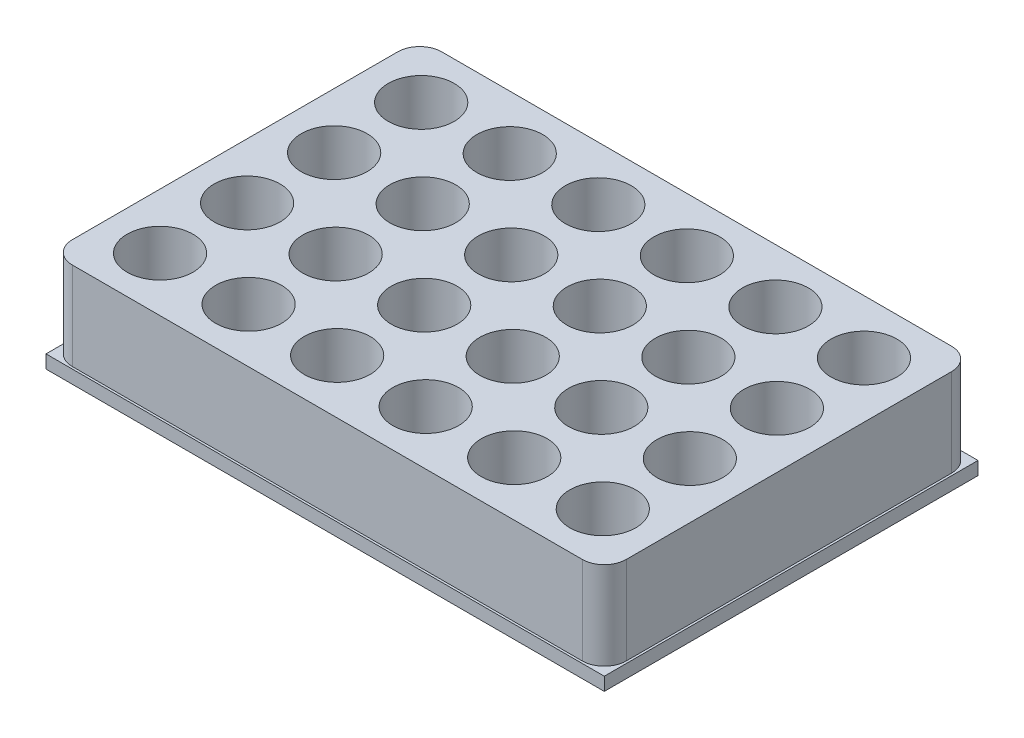
SolidWorks part; units mm, degrees
ref_plane "Front Plane" through (0, 0, 0) normal (0, 0, 1) x (1, 0, 0)
ref_plane "Top Plane" through (0, 0, 0) normal (0, 1, 0) x (1, 0, 0)
ref_plane "Right Plane" through (0, 0, 0) normal (1, 0, 0) x (0, 0, -1)
sketch "Sketch1" plane through (0, 0, 0) normal (0, 1, 0) x (1, 0, 0)
  line L0 (0, 0) -> (0, 12.3) construction
  line L1 (0, 0) -> (125.98, 0)
  line L2 (0, 0) -> (0, 84)
  line L3 (0, 84) -> (125.98, 84)
  line L4 (125.98, 0) -> (125.98, 84)
  line L6 (5.14, 71.7) -> (5.14, 88.6496) construction
  line L7 (12.64, 79.2) -> (-12.5993, 79.2) construction
  circle A0 centre (12.64, 12.3) radius 7.5
  circle A1 centre (32.78, 12.3) radius 7.5
  circle A2 centre (52.92, 12.3) radius 7.5
  circle A3 centre (73.06, 12.3) radius 7.5
  circle A4 centre (93.2, 12.3) radius 7.5
  circle A5 centre (113.34, 12.3) radius 7.5
  circle A6 centre (32.78, 32.1) radius 7.5
  circle A7 centre (52.92, 32.1) radius 7.5
  circle A8 centre (73.06, 32.1) radius 7.5
  circle A9 centre (93.2, 32.1) radius 7.5
  circle A10 centre (113.34, 32.1) radius 7.5
  circle A11 centre (32.78, 51.9) radius 7.5
  circle A12 centre (52.92, 51.9) radius 7.5
  circle A13 centre (73.06, 51.9) radius 7.5
  circle A14 centre (93.2, 51.9) radius 7.5
  circle A15 centre (113.34, 51.9) radius 7.5
  circle A16 centre (32.78, 71.7) radius 7.5
  circle A17 centre (52.92, 71.7) radius 7.5
  circle A18 centre (73.06, 71.7) radius 7.5
  circle A19 centre (93.2, 71.7) radius 7.5
  circle A20 centre (113.34, 71.7) radius 7.5
  circle A21 centre (12.64, 32.1) radius 7.5
  circle A22 centre (12.64, 51.9) radius 7.5
  circle A23 centre (12.64, 71.7) radius 7.5
  dimension "D5" = 6
  dimension "D7" = 15
  dimension "D1" = 125.98
  dimension "D2" = 84
  dimension "D3" = 12.3
  dimension "D4" = 12.64
  dimension "D8" = 5.14
  dimension "D9" = 4.8
  dimension "D6" = 4
extrude "Boss-Extrude1" add sketch "Sketch1" along normal blind 20
sketch "Sketch2" plane through (0, 0, 0) normal (0, -1, 0) x (1, 0, 0)
  line L0 (0, 0) -> (-0.5, 0) construction
  line L1 (-0.5, 0) -> (-0.5, 0.5) construction
  line L2 (125.98, -84) -> (125.98, -84.5)
  line L3 (125.98, -84.5) -> (126.48, -84.5)
  line L5 (-0.5, 0.5) -> (126.48, 0.5)
  line L6 (-0.5, 0.5) -> (-0.5, -84.5)
  line L7 (-0.5, -84.5) -> (126.48, -84.5)
  line L8 (126.48, 0.5) -> (126.48, -84.5)
  dimension "D1" = 0.5
  dimension "D2" = 0.5
  dimension "D3" = 0.5
  dimension "D4" = 0.5
extrude "Boss-Extrude3" add sketch "Sketch2" along normal blind 3 contours L6 L5 L8 L7
fillet "Fillet2" radius 5 4 edges at (0, 10, -84) (125.98, 10, -84) (125.98, 10, 0) (0, 10, 0)
